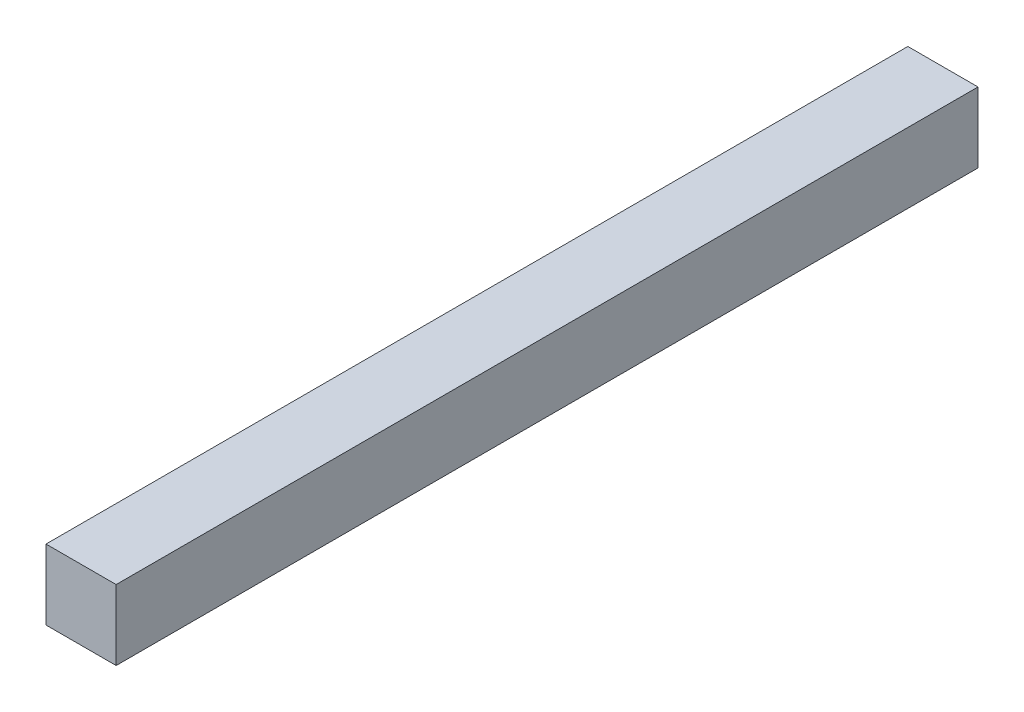
SolidWorks part; units mm, degrees
ref_plane "Plan de face" through (0, 0, 0) normal (0, 0, 1) x (1, 0, 0)
ref_plane "Plan de dessus" through (0, 0, 0) normal (0, 1, 0) x (1, 0, 0)
ref_plane "Plan de droite" through (0, 0, 0) normal (1, 0, 0) x (0, 0, -1)
sketch "Esquisse1" plane through (0, 0, 0) normal (0, 0, 1) x (1, 0, 0)
  line L1 (0, 0) -> (70, 0)
  line L2 (0, 0) -> (0, 70)
  line L3 (0, 70) -> (70, 70)
  line L4 (70, 0) -> (70, 70)
  dimension "D1" = 70
  dimension "D2" = 70
extrude "Boss.-Extru.1" add sketch "Esquisse1" along normal blind 860
sketch "Esquisse2" plane through (0, 0, 0) normal (0, 0, -1) x (-1, 0, 0)
  line L0 (-70, 35) -> (0, 35) construction
  line L1 (-70, 0) -> (-70, 70) construction
  line L2 (0, 70) -> (0, 0) construction
  circle A0 centre (-35, 35) radius 6
  dimension "D1" = 12
extrude "Enlèv. mat.-Extru.1" cut sketch "Esquisse2" against normal blind 80
